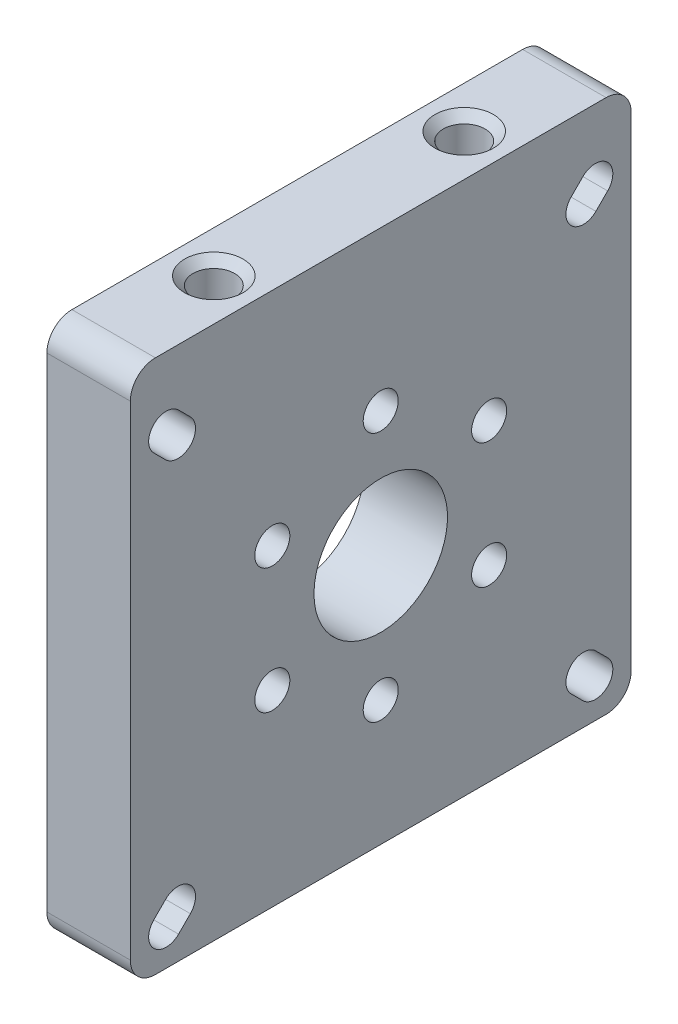
SolidWorks part; units mm, degrees
material "1060 Сплав"
ref_plane "Спереди" through (0, 0, 0) normal (0, 0, 1) x (1, 0, 0)
ref_plane "Сверху" through (0, 0, 0) normal (0, 1, 0) x (1, 0, 0)
ref_plane "Справа" through (0, 0, 0) normal (1, 0, 0) x (0, 0, -1)
sketch "Эскиз1" plane through (0, 0, 0) normal (0, 0, 1) x (1, 0, 0)
  line L0 (0, 8) -> (0, 50)
  line L1 (0, 50) -> (10, 50)
  line L2 (10, 50) -> (10, 8)
  line L3 (10, 8) -> (0, 8)
  line L4 (-29.3651, 0) -> (90.6978, 0) construction
  dimension "D1" = 16
  dimension "D2" = 100
  dimension "D3" = 10
revolve "Повернуть1" add sketch "Эскиз1" angle 360 about L4
sketch "Эскиз7" plane through (0, 0, 0) normal (-1, 0, 0) x (0, 0, 1)
  line L1 (30, -30) -> (-30, -30)
  line L2 (30, -30) -> (30, 34)
  line L3 (30, 34) -> (-30, 34)
  line L4 (-30, -30) -> (-30, 34)
  circle A0 centre (0, 0) radius 50 construction
  circle A1 centre (0, 0) radius 50
  point P0 (0, 0)
  dimension "D1" = 60
  dimension "D2" = 64
  dimension "D3" = 30
  dimension "D4" = 30
extrude "Вырез-Вытянуть4" cut sketch "Эскиз7" against normal through all both and the other way through all
sketch "Эскиз5" plane through (0, 0, 0) normal (-1, 0, 0) x (0, 0, 1)
  line L0 (0, 0) -> (0, 20) construction
  line L1 (0, 0) -> (0, 27.198) construction
  line L5 (0, 0) -> (50000, 0) construction
  circle A0 centre (0, 0) radius 15 construction
  circle A4 centre (0, 15) radius 2.1
  point P14 (0, 0)
  dimension "D1" = 30
  dimension "D2" = 4.2
  dimension "D3" = 0
extrude "Вырез-Вытянуть2" cut sketch "Эскиз5" against normal up to next
pattern_circular "Круговой массив1" count 6 over 360 about axis through (0, 0, 0) along (1, 0, 0) of "Вырез-Вытянуть2"
sketch "Эскиз6" plane through (0, 0, 0) normal (-1, 0, 0) x (0, 0, 1)
  line L0 (-27.192, 24.2222) -> (-25.7778, 22.808)
  line L1 (-24.2222, 27.192) -> (-22.808, 25.7778)
  line L2 (0, 0) -> (0, 50000) construction
  line L4 (-26.4849, 23.5151) -> (-23.5151, 26.4849) construction
  line L5 (-15.9099, 15.9099) -> (35339.4292, -35339.4292) construction
  arc A0 (-24.2222, 27.192) -> (-27.192, 24.2222) centre (-25.7071, 25.7071) ccw
  arc A1 (-25.7778, 22.808) -> (-22.808, 25.7778) centre (-24.2929, 24.2929) ccw
  circle A2 centre (0, 0) radius 35.3553 construction
  point P11 (-25, 25)
  dimension "D1" = 2
  dimension "D3" = 25
  dimension "D2" = 4.2
  dimension "D4" = 45
extrude "Вырез-Вытянуть3" cut sketch "Эскиз6" against normal through all both and the other way through all
pattern_circular "Круговой массив2" count 4 over 360 about axis through (0, 0, 0) along (1, 0, 0) of "Вырез-Вытянуть3"
sketch "Эскиз10" plane through (0, 34, 0) normal (0, 1, 0) x (1, 0, 0)
  line L2 (0, 30) -> (0, -30) construction
  point P0 (5, 15)
  point P14 (5, -15)
  dimension "D1" = 5
  dimension "D2" = 15
  dimension "D3" = 30
hole_wizard "Отверстие обработанное метчиком M61" positions "Эскиз10" profile "Эскиз9" tap size "M6" standard "IS"
cosmetic thread "Отверстие резьбы1" parameters "D1"=12, "D2"=6
cosmetic thread "Отверстие резьбы2" parameters "D1"=12, "D2"=6
sketch "Эскиз9" plane through (5, 34, -15) normal (1, 0, 0) x (0, 0, 1)
  line L0 (0, 0) -> (0, 18.5022)
  line L1 (0, 18.5022) -> (2.5, 17)
  line L2 (2.5, 17) -> (2.5, 1)
  line L3 (2.5, 1) -> (3.5, 0)
  line L5 (3.5, 0) -> (0, 0)
  line L6 (-2.5, 1) -> (-3.5, 0) construction
  line L10 (0, 18.5022) -> (-2.5, 17) construction
  line L11 (0, -6.35) -> (0, 107.95) construction
  dimension "Диаметр сверла" = 5
  dimension "Глубина сверла" = 17
  dimension "Диаметр передней зенковки" = 7
  dimension "Угол передней зенковки" = 90
  dimension "Угол заточки сверла" = 118
chamfer "Фаска1" distance 2 angle 45 6 edges at (0, 5.6813, 14.0404) (0, -9.3187, 11.9404) (0, -15, -2.1) (0, -5.6813, -14.0404) (0, 9.3187, -11.9404) (0, 15, 2.1)
fillet "Скругление1" radius 3 4 edges at (5, -30, -30) (5, -30, 30) (5, 34, 30) (5, 34, -30)
